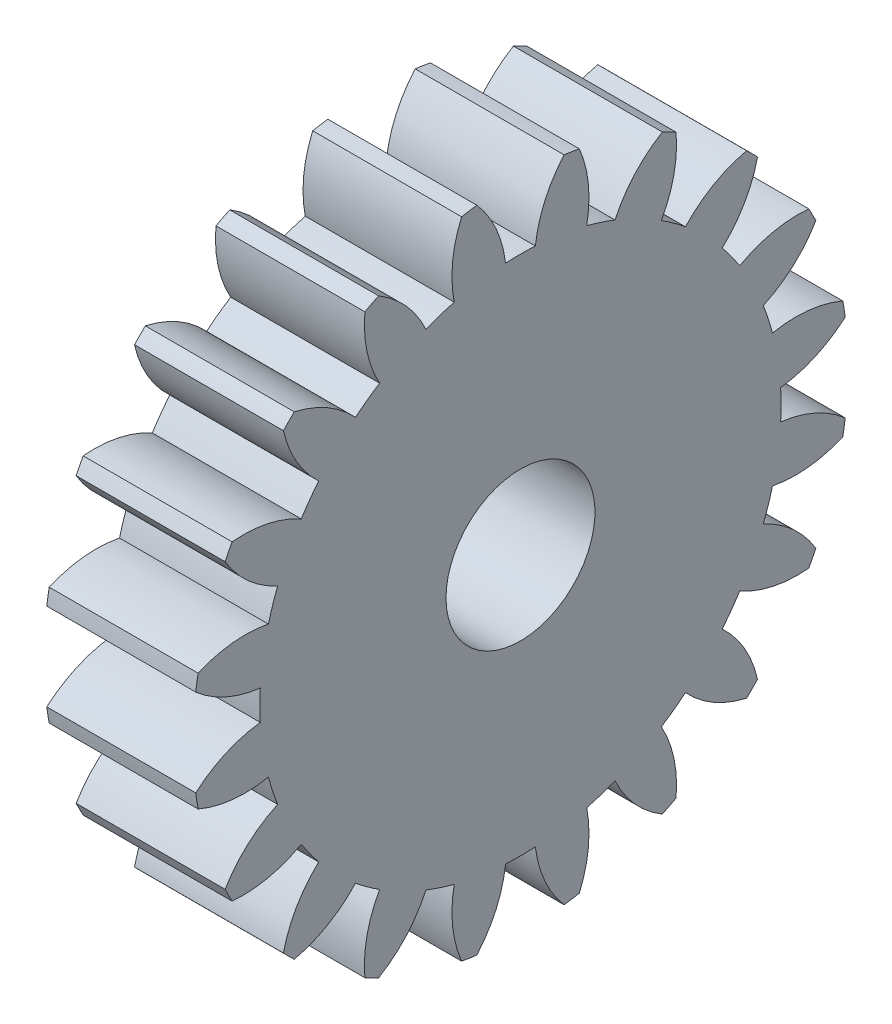
SolidWorks part; units mm, degrees
ref_plane "Plane1" through (0, 0, 0) normal (0, 0, 1) x (1, 0, 0)
ref_plane "Plane2" through (0, 0, 0) normal (0, 1, 0) x (1, 0, 0)
ref_plane "Plane3" through (0, 0, 0) normal (1, 0, 0) x (0, 0, -1)
sketch "HoldingSke" plane through (0, 0, 0) normal (0, 1, 0) x (1, 0, 0)
  line L0 (0, 0) -> (0.9397, -0.342)
  line L1 (-15, 0) -> (100, 0) construction
  line L2 (0, 0) -> (-2.1039, 2.3779)
  line L3 (0, 0) -> (-11.863, 4.5341)
  line L4 (0, 0) -> (8.1152, 2.9537)
  line L5 (0, 0) -> (-46.8476, -17.4728)
  line L6 (0, 0) -> (-4.1448, -2.7965)
  line L7 (-2.1039, 2.3779) -> (8.6586, 51.2059)
  line L8 (-76.2, 54.61) -> (-75.3, 54.61)
  line L9 (-71.009, 38.7566) -> (-53.1078, 45.2721)
  line L10 (-76.2, 71.12) -> (104.1128, 71.12)
  line L11 (0, 0) -> (-5, 0)
  line L12 (-76.2, 101.6) -> (-76.162, 101.6)
  line L13 (24.9733, 27.94) -> (52.9518, 28.4284)
  line L14 (24.9733, 27.94) -> (24.9743, 27.94)
  line L15 (24.9733, 27.94) -> (100.4006, 29.5858)
  line L16 (-63.627, -1) -> (-12.827, -1)
  circle A0 centre (0, 0) radius 2.5
  circle A1 centre (0, 0) radius 8.749
  circle A2 centre (0, 0) radius 37.5
  circle A3 centre (0, 0) radius 2.5
  dimension "MHD" = 17.498
  dimension "Hub_dia" = 75
  dimension "Bore" = 5
  dimension "MBD" = 5
  dimension "Num_teeth" = 20
  dimension "Pitch" = 1
  dimension "Overall_len" = 50
  dimension "Show_teeth" = 20
  dimension "Thickness" = 5
  dimension "OAL" = 50.0001
  dimension "T_dim" = 0.9
  dimension "Ap" = 20
  dimension "H" = 19.05
  dimension "Pitch_radius" = 180.3128
  dimension "Width" = 5
  dimension "Backlash" = 0.038
  dimension "Addendum_fac" = 1
  dimension "Dedendum_fac" = 1.25
  dimension "Clearance_fac" = 0.25
  dimension "Dedendum_add" = 0.001
  dimension "Module" = 1
sketch "BasProSke" plane through (0, 0, 0) normal (0, 1, 0) x (1, 0, 0)
  line L0 (-10, 0) -> (60, 0) construction
  line L1 (0, 0) -> (0, 11)
  line L2 (0, 0) -> (5, 0)
  line L3 (5, 0) -> (5, 11)
  line L4 (5, 11) -> (0, 11)
  dimension "Thickness" = 5
  dimension "Diameter" = 22
revolve "Base-Revolve" add sketch "BasProSke" angle 360 about L0
sketch "TooCutSke" plane through (0, 0, 0) normal (1, 0, 0) x (0, 0, -1)
  line L1 (0, 0) -> (0, 107) construction
  line L2 (0, 0) -> (-0.8511, 9.9637) construction
  line L3 (0, 0) -> (-3.1206, 19.7028) construction
  line L4 (-0.8511, 9.9637) -> (-1.5603, 9.8514) construction
  arc A0 (0.4999, 8.7347) -> (-0.4999, 8.7347) centre (0, 0) ccw
  arc A1 (1.4852, 10.9249) -> (-1.4852, 10.9249) centre (0, 0) ccw
  circle A2 centre (0, 0) radius 10 construction
  circle A3 centre (0, 0) radius 9.3969 construction
  arc A4 (-0.4999, 8.7347) -> (-1.4852, 10.9249) centre (-4.4722, 8.2645) ccw
  arc A5 (1.4852, 10.9249) -> (0.4999, 8.7347) centre (4.4722, 8.2645) ccw
  dimension "Root_dia" = 17.498
  dimension "Overcut_dia" = 22.0508
  dimension "Pitch_dia" = 20
  dimension "Base_dia" = 18.7939
  dimension "Flank_rad" = 4
  dimension "Half_ang" = 9
  dimension "Half_CT" = 0.7181
extrude "ToothCut" cut sketch "TooCutSke" along normal through all
fillet "Breaks" [suppressed] radius 0.02
fillet "RootFillets" [suppressed] radius 0.251
pattern_circular "TeethCuts" count 20 every 18 about axis through (-10, 0, 0) along (1, 0, 0) of "ToothCut", "RootFillets", "Breaks"
sketch "HubNeaOneSke" plane through (0, 0, 0) normal (-1, 0, 0) x (0, 0, 1)
  circle A0 centre (0, 0) radius 8.749
  dimension "Diameter" = 17.498
extrude "HubNearOne" [suppressed] add sketch "HubNeaOneSke" along normal blind 45.0001
sketch "HubNeaBotSke" plane through (0, 0, 0) normal (-1, 0, 0) x (0, 0, 1)
  circle A0 centre (0, 0) radius 8.749
  dimension "Diameter" = 17.498
extrude "HubNearBoth" [suppressed] add sketch "HubNeaBotSke" along normal blind 22.5
ref_plane "FarPln" through (5, 0, 0) normal (1, 0, 0) x (0, 0, -1)
sketch "HubFarSke" plane through (5, 0, 0) normal (1, 0, 0) x (0, 0, -1)
  circle A0 centre (0, 0) radius 8.749
  dimension "Diameter" = 17.498
extrude "HubFar" [suppressed] add sketch "HubFarSke" along normal blind 22.5
sketch "BorSke" plane through (0, 0, 0) normal (1, 0, 0) x (0, 0, -1)
  circle A0 centre (0, 0) radius 2.5
  dimension "Diameter" = 5
extrude "Bore" cut sketch "BorSke" along normal mid plane 100.0001
sketch "KeySke" plane through (0, 0, 0) normal (1, 0, 0) x (0, 0, -1)
  line L0 (-1, 0) -> (-1, 3.4)
  line L1 (-1, 3.4) -> (1, 3.4)
  line L2 (1, 3.4) -> (1, 0)
  line L3 (0, 0) -> (0, 34) construction
  line L4 (-1, 0) -> (1, 0)
  dimension "Offset" = 3.4
  dimension "Width" = 2
extrude "Keyway" [suppressed] cut sketch "KeySke" along normal mid plane 100.0001
pattern_circular "Keyway2" [suppressed] count 2 every 90 about axis through (-10, 0, 0) along (1, 0, 0)
sketch "草圖2" plane through (5, 0, 0) normal (1, 0, 0) x (0, 0, -1)
  line L1 (4.6188, 0) -> (2.3094, 4)
  line L2 (2.3094, 4) -> (-2.3094, 4)
  line L3 (-2.3094, 4) -> (-4.6188, 0)
  line L4 (-4.6188, 0) -> (-2.3094, -4)
  line L5 (-2.3094, -4) -> (2.3094, -4)
  line L6 (2.3094, -4) -> (4.6188, 0)
  circle A0 centre (0, 0) radius 4 construction
  dimension "D1" = 8
equation "' \"Module@HoldingSke\" = 6.35"
equation "' \"Num_teeth@HoldingSke\" = 12"
equation "' \"Ap@HoldingSke\" =  20"
equation "' \"Ap@HoldingSke\" = 20"
equation "' \"Width@HoldingSke\" = 0.5 * 25.4"
equation "' \"Hub_dia@HoldingSke\"= 1 * 25.4"
equation "' \"Hub_dia@HoldingSke\" = 1 * 25.4"
equation "' \"Overall_len@HoldingSke\" = 1.0 * 25.4"
equation "' \"Bore@HoldingSke\" = 0.75 * 25.4"
equation "' \"T_dim@HoldingSke\" = 0.1 * 25.4"
equation "' \"Width@KeySke\" = 0.25 * 25.4"
equation "' \"Show_teeth@HoldingSke\" = 13"
equation "' \"Backlash@HoldingSke\" = 0.009 * 25.4"
equation "' \"Addendum_fac@HoldingSke\" = 1.0"
equation "' \"Dedendum_fac@HoldingSke\" = 1.25"
equation "' \"Dedendum_add@HoldingSke\" = 0.00005 * 25.4"
equation "' \"Clearance_fac@HoldingSke\" = 0.25"
equation "\"Pitch@HoldingSke\" = 1 / \"Module@HoldingSke\""
equation "\"Overcut_dia@TooCutSke\" = (\"Num_teeth@HoldingSke\" + 2 * \"Addendum_fac@HoldingSke\") / \"Pitch@HoldingSke\" + 0.002 * 25.4"
equation "\"Pitch_dia@TooCutSke\" = \"Num_teeth@HoldingSke\" / \"Pitch@HoldingSke\""
equation "\"Base_dia@TooCutSke\" = \"Num_teeth@HoldingSke\" / \"Pitch@HoldingSke\" * cos((\"Ap@HoldingSke\"  * 3.14159265 / 180))"
equation "\"Root_dia@TooCutSke\" = (\"Num_teeth@HoldingSke\" + 2) / \"Pitch@HoldingSke\" - 2 * (\"Addendum_fac@HoldingSke\" + \"Dedendum_fac@HoldingSke\") / \"Pitch@HoldingSke\" - \"Dedendum_add@HoldingSke\" * 2"
equation "\"Half_ang@TooCutSke\" = 180 / \"Num_teeth@HoldingSke\""
equation "\"Half_CT@TooCutSke\" = \"Num_teeth@HoldingSke\" / \"Pitch@HoldingSke\" * sin((3.14159265 / 2 / \"Num_teeth@HoldingSke\")) / 2 - 7 * \"Backlash@HoldingSke\" / 4"
equation "\"Flank_rad@TooCutSke\" = \"Num_teeth@HoldingSke\" / \"Pitch@HoldingSke\" / 5"
equation "\"Radius@RootFillets\" = \"Clearance_fac@HoldingSke\" / \"Pitch@HoldingSke\" + \"Dedendum_add@HoldingSke\""
equation "\"Break_rad@Breaks\" = 0.02 / \"Pitch@HoldingSke\""
equation "\"Thickness@HoldingSke\" = \"Width@HoldingSke\""
equation "\"OAL@HoldingSke\" = \"Thickness@HoldingSke\""
equation "\"MHD@HoldingSke\" = (\"Num_teeth@HoldingSke\" + 2) / \"Pitch@HoldingSke\" - 2 * (\"Addendum_fac@HoldingSke\" + \"Dedendum_fac@HoldingSke\")  / \"Pitch@HoldingSke\" - \"Dedendum_add@HoldingSke\" * 2"
equation "\"MBD@HoldingSke\" = (\"Num_teeth@HoldingSke\" + 2) / \"Pitch@HoldingSke\" - 2 * (\"Addendum_fac@HoldingSke\" + \"Dedendum_fac@HoldingSke\")  / \"Pitch@HoldingSke\" - \"Dedendum_add@HoldingSke\" * 2 - 0.002 * 25.4"
equation "\"MHD@HoldingSke\" = ((sgn( \"MHD@HoldingSke\" - \"Hub_dia@HoldingSke\" )-1)*( \"MHD@HoldingSke\" - \"Hub_dia@HoldingSke\" ))/-2+ \"Hub_dia@HoldingSke\""
equation "\"MBD@HoldingSke\" = ((sgn( \"MBD@HoldingSke\" - \"Bore@HoldingSke\" )-1)*( \"MBD@HoldingSke\" - \"Bore@HoldingSke\" ))/-2+ \"Bore@HoldingSke\""
equation "\"OAL@HoldingSke\" = ((sgn( \"OAL@HoldingSke\" - \"Overall_len@HoldingSke\" )+1)*( \"OAL@HoldingSke\" - \"Overall_len@HoldingSke\" ))/2 + \"Overall_len@HoldingSke\" + 0.000002 * 25.4"
equation "\"Num_teeth@TeethCuts\" = int( \"Show_teeth@HoldingSke\" ) + 1"
equation "\"Num_teeth@TeethCuts\" = ((sgn( \"Num_teeth@TeethCuts\" - \"Num_teeth@HoldingSke\" )-1)*( \"Num_teeth@TeethCuts\" - \"Num_teeth@HoldingSke\" ))/-2+ \"Num_teeth@HoldingSke\""
equation "\"Num_teeth@TeethCuts\" = ((sgn( \"Num_teeth@TeethCuts\" - 2.0)+1)*( \"Num_teeth@TeethCuts\" - 2.0))/2 +2.0"
equation "\"Angle@TeethCuts\" = 360.0 / \"Num_teeth@HoldingSke\""
equation "\"Diameter@BasProSke\" = (\"Num_teeth@HoldingSke\" + 2 * \"Addendum_fac@HoldingSke\") / \"Pitch@HoldingSke\""
equation "\"Thickness@BasProSke\"  = \"Thickness@HoldingSke\""
equation "' \"Fillet_rad@BasProSke\" =  \"Thickness@HoldingSke\" * 0.05"
equation "' \"Fillet_rad@BasProSke\" = \"Thickness@HoldingSke\" * 0.05"
equation "\"MHD@HoldingSke\" = ((sgn( \"MHD@HoldingSke\" - \"Root_dia@TooCutSke\" )-1)*( \"MHD@HoldingSke\" - \"Root_dia@TooCutSke\" ))/-2+ \"Root_dia@TooCutSke\""
equation "\"Diameter@HubNeaOneSke\" = \"MHD@HoldingSke\""
equation "\"Length@HubNearOne\" = \"OAL@HoldingSke\" - \"Thickness@BasProSke\""
equation "\"Diameter@HubNeaBotSke\" = \"MHD@HoldingSke\""
equation "\"Length@HubNearBoth\" = ( \"OAL@HoldingSke\" - \"Thickness@BasProSke\" ) / 2.0"
equation "\"Thickness@FarPln\" = \"Thickness@BasProSke\""
equation "\"Diameter@HubFarSke\" = \"MHD@HoldingSke\""
equation "\"Length@HubFar\" = ( \"OAL@HoldingSke\" - \"Thickness@BasProSke\" ) / 2.0"
equation "\"Diameter@BorSke\" = \"MBD@HoldingSke\""
equation "\"D1@Bore\" = \"OAL@HoldingSke\" * 2.0"
equation "\"D1@Keyway\" = \"OAL@HoldingSke\" * 2.0"
equation "\"Offset@KeySke\" = \"T_dim@HoldingSke\" + \"MBD@HoldingSke\" / 2.0"
